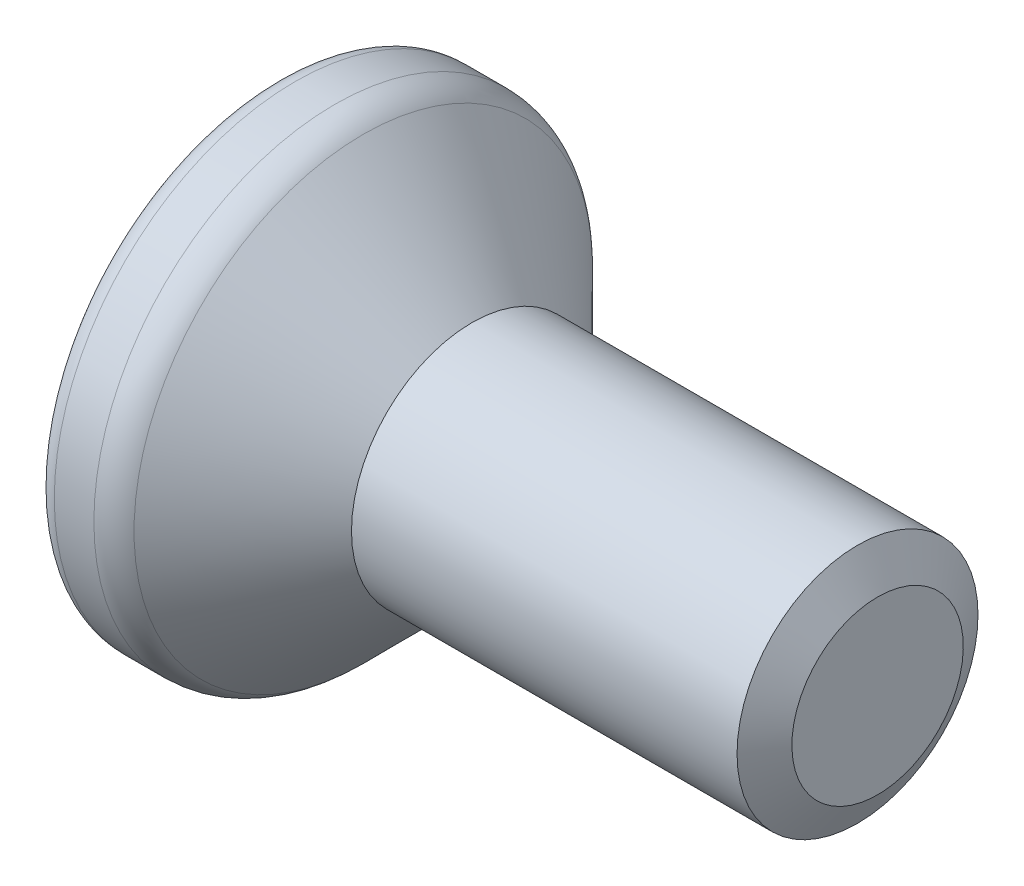
SolidWorks part; units mm, degrees
ref_plane "前视基准面" through (0, 0, 0) normal (0, 0, 1) x (1, 0, 0)
ref_plane "上视基准面" through (0, 0, 0) normal (0, 1, 0) x (1, 0, 0)
ref_plane "右视基准面" through (0, 0, 0) normal (1, 0, 0) x (0, 0, -1)
sketch "草图1" plane through (0, 0, 0) normal (0, 0, 1) x (1, 0, 0)
  line L0 (7.5, 0) -> (-7.5, 0)
  line L1 (-7.5, 0) -> (-7.5, 6)
  line L2 (-7.5, 6) -> (-5.6, 6)
  line L3 (-5.6, 6) -> (-2.6, 3)
  line L4 (-2.6, 3) -> (7.5, 3)
  line L5 (7.5, 3) -> (7.5, 0)
  point P5 (0, 0)
  dimension "D1" = 4.9
  dimension "D2" = 6
  dimension "D3" = 3
  dimension "D4" = 45
  dimension "D5" = 15
revolve "旋转1" add sketch "草图1" angle 360 about L0
fillet "圆角1" radius 0.5 1 edges at (-7.5, 6, 0)
fillet "圆角2" radius 1 1 edges at (-5.6, 6, 0)
sketch "草图2" plane through (-7.5, 0, 0) normal (-1, 0, 0) x (0, 0, 1)
  line L1 (0, 2.3094) -> (-2, 1.1547)
  line L2 (-2, 1.1547) -> (-2, -1.1547)
  line L3 (-2, -1.1547) -> (0, -2.3094)
  line L4 (0, -2.3094) -> (2, -1.1547)
  line L5 (2, -1.1547) -> (2, 1.1547)
  line L6 (2, 1.1547) -> (0, 2.3094)
  circle A0 centre (0, 0) radius 2 construction
  dimension "D1" = 4
extrude "切除-拉伸1" cut sketch "草图2" against normal blind 2.5
chamfer "倒角1" distance 0.5 angle 60 1 edges at (7.5, 3, 0)
